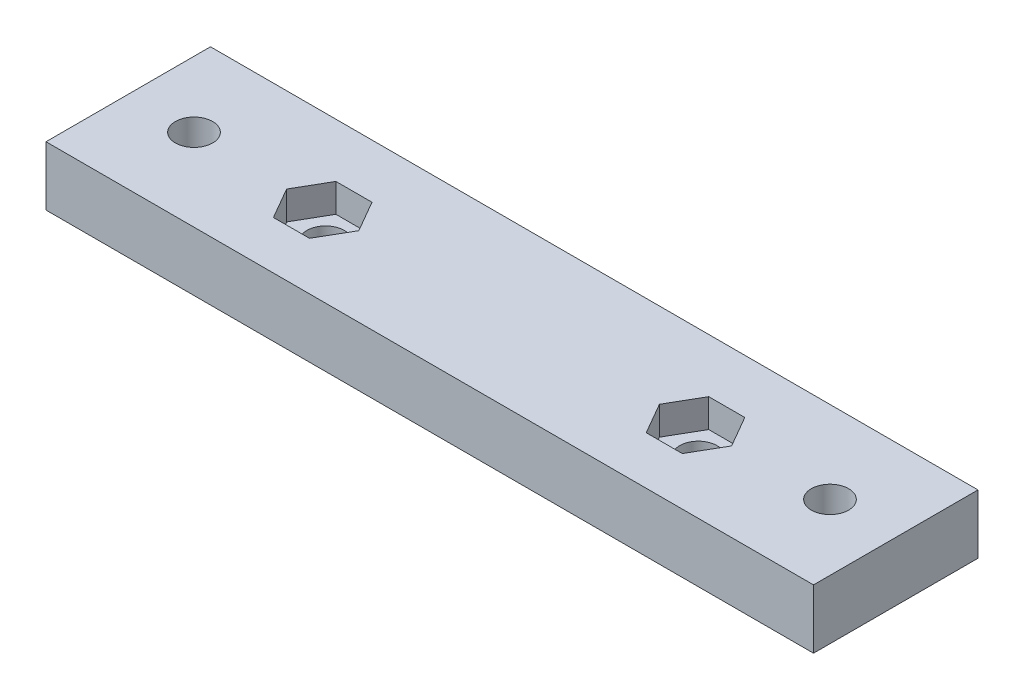
SolidWorks part; units mm, degrees
ref_plane "Front Plane" through (0, 0, 0) normal (0, 0, 1) x (1, 0, 0)
ref_plane "Top Plane" through (0, 0, 0) normal (0, 1, 0) x (1, 0, 0)
ref_plane "Right Plane" through (0, 0, 0) normal (1, 0, 0) x (0, 0, -1)
sketch "Sketch1" plane through (0, 0, 0) normal (0, 1, 0) x (1, 0, 0)
  line L1 (-35, -7.5) -> (35, -7.5)
  line L2 (-35, -7.5) -> (-35, 7.5)
  line L3 (-35, 7.5) -> (35, 7.5)
  line L4 (35, -7.5) -> (35, 7.5)
  line L5 (-35, -7.5) -> (35, 7.5) construction
  line L6 (-35, 7.5) -> (35, -7.5) construction
  point P0 (0, 0)
  dimension "D1" = 70
  dimension "D2" = 15
extrude "Boss-Extrude1" add sketch "Sketch1" along normal blind 5.4
sketch "Sketch2" plane through (0, 5.4, 0) normal (0, 1, 0) x (1, 0, 0)
  line L0 (-35, 7.5) -> (-35, -7.5) construction
  line L1 (35, -7.5) -> (35, 7.5) construction
  line L2 (-35, -7.5) -> (35, -7.5) construction
  line L3 (-15.3546, 2.5866) -> (-18.6454, 2.5866)
  line L4 (-18.6454, 2.5866) -> (-20.2909, -0.2634)
  line L5 (-20.2909, -0.2634) -> (-18.6454, -3.1134)
  line L6 (-18.6454, -3.1134) -> (-15.3546, -3.1134)
  line L7 (-15.3546, -3.1134) -> (-13.7091, -0.2634)
  line L8 (-13.7091, -0.2634) -> (-15.3546, 2.5866)
  line L9 (0, 15.871) -> (0, -16.3989) construction
  line L10 (13.7091, -0.2634) -> (15.3546, 2.5866)
  line L11 (15.3546, -3.1134) -> (13.7091, -0.2634)
  line L12 (18.6454, -3.1134) -> (15.3546, -3.1134)
  line L13 (20.2909, -0.2634) -> (18.6454, -3.1134)
  line L14 (18.6454, 2.5866) -> (20.2909, -0.2634)
  line L15 (15.3546, 2.5866) -> (18.6454, 2.5866)
  circle A0 centre (-29, -0.2634) radius 1.7
  circle A1 centre (-17, -0.2634) radius 1.7
  circle A2 centre (17, -0.2634) radius 1.7
  circle A3 centre (29, -0.2634) radius 1.7
  circle A4 centre (-17, -0.2634) radius 2.85 construction
  circle A5 centre (17, -0.2634) radius 2.85 construction
  circle A6 centre (17, -0.2634) radius 1.7
  point P12 (-17, 2.5866)
  dimension "D1" = 6
  dimension "D6" = 3.4
  dimension "D2" = 6
  dimension "D3" = 12
  dimension "D4" = 12
  dimension "D5" = 34
  dimension "D7" = 5.7
extrude "Cut-Extrude1" cut sketch "Sketch2" against normal blind 2.6 contours L3 L4 L5 L6 L7 L8 | L10 L15 L14 L13 L12 L11
sketch "Sketch4" plane through (0, 5.4, 0) normal (0, 1, 0) x (1, 0, 0)
  line L12 (-35, 7.5) -> (-35, -7.5) construction
  line L14 (0, 10.8413) -> (0, -11.6036) construction
  circle A0 centre (-29, 0) radius 1.7
  circle A3 centre (-17, 0) radius 1.7
  circle A7 centre (17, 0) radius 1.7
  circle A8 centre (29, 0) radius 1.7
  dimension "D4" = 3.4
  dimension "D1" = 6
  dimension "D2" = 12
extrude "Cut-Extrude3" cut sketch "Sketch4" against normal blind 5.4
